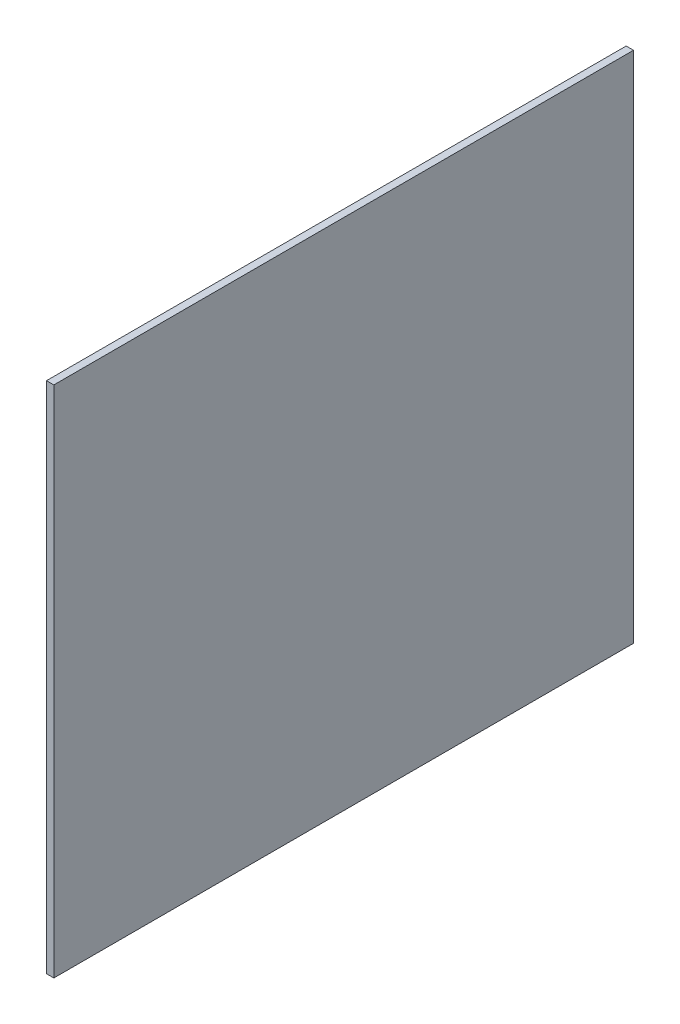
SolidWorks part; units mm, degrees
ref_plane "Alzado" through (0, 0, 0) normal (0, 0, 1) x (1, 0, 0)
ref_plane "Planta" through (0, 0, 0) normal (0, 1, 0) x (1, 0, 0)
ref_plane "Vista lateral" through (0, 0, 0) normal (1, 0, 0) x (0, 0, -1)
sketch "Croquis1" plane through (0, 0, 0) normal (1, 0, 0) x (0, 0, -1)
  line L1 (-141.3303, -63.8704) -> (253.6697, -63.8704)
  line L2 (-141.3303, -63.8704) -> (-141.3303, 286.1296)
  line L3 (-141.3303, 286.1296) -> (253.6697, 286.1296)
  line L4 (253.6697, -63.8704) -> (253.6697, 286.1296)
  dimension "D1" = 395
  dimension "D2" = 350
extrude "Saliente-Extruir1" add sketch "Croquis1" along normal blind 5
